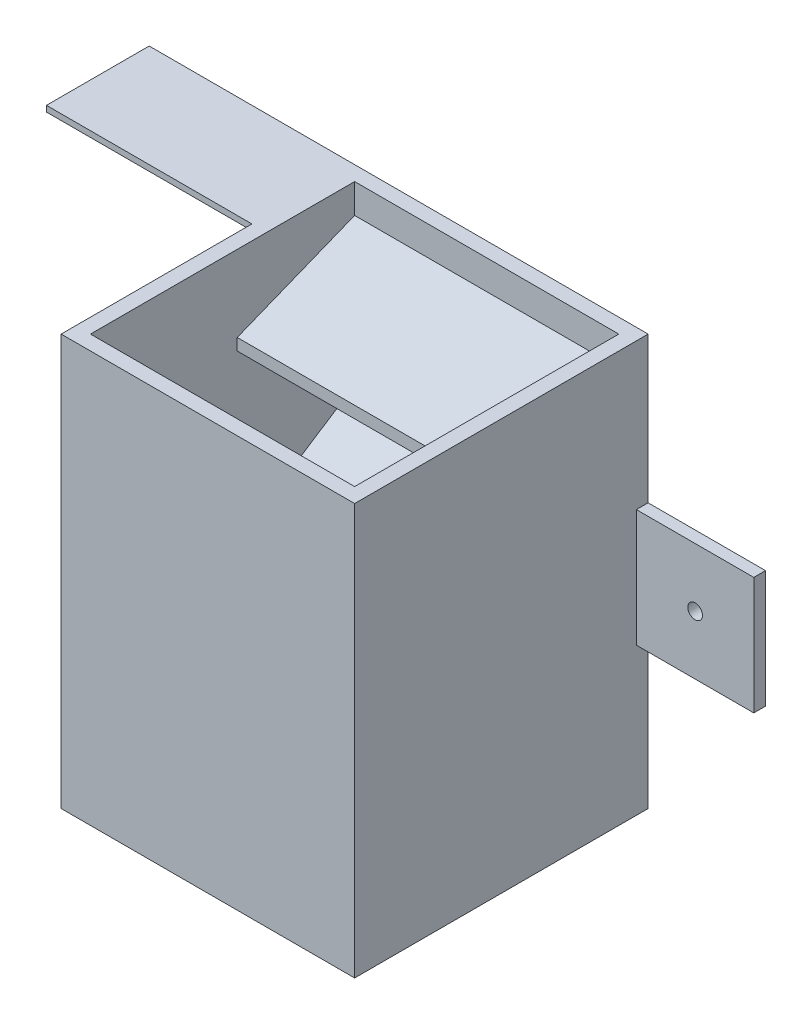
SolidWorks part; units mm, degrees
material "ABS"
ref_plane "Alzado" through (0, 0, 0) normal (0, 0, 1) x (1, 0, 0)
ref_plane "Planta" through (0, 0, 0) normal (0, 1, 0) x (1, 0, 0)
ref_plane "Vista lateral" through (0, 0, 0) normal (1, 0, 0) x (0, 0, -1)
sketch "Croquis2" plane through (0, 0, 0) normal (0, 1, 0) x (1, 0, 0)
  line L0 (-36.1972, 28.2218) -> (-36.1972, -21.7782)
  line L1 (-36.1972, -21.7782) -> (13.8028, -21.7782)
  line L2 (13.8028, -21.7782) -> (13.8028, 28.2218)
  line L3 (13.8028, 28.2218) -> (-36.1972, 28.2218)
  dimension "D1" = 50
  dimension "D2" = 50
extrude "Saliente-Extruir1" add sketch "Croquis2" along normal blind 70
sketch "Croquis3" plane through (0, 70, 0) normal (0, 1, 0) x (1, 0, 0)
  line L0 (-11.1972, 28.2218) -> (-11.1972, 25.7218) construction
  line L1 (13.8028, 28.2218) -> (-36.1972, 28.2218) construction
  line L2 (11.3028, 25.7218) -> (-33.6972, 25.7218)
  line L3 (-33.6972, 25.7218) -> (-33.6972, -19.2782)
  line L4 (-33.6972, -19.2782) -> (11.3028, -19.2782)
  line L5 (11.3028, -19.2782) -> (11.3028, 25.7218)
  point P7 (-11.1972, 25.7218)
  dimension "D1" = 2.5
  dimension "D2" = 45
  dimension "D3" = 45
extrude "Cortar-Extruir1" cut sketch "Croquis3" against normal blind 130
sketch "Croquis4" plane through (0, 0, -25.7218) normal (0, 0, 1) x (1, 0, 0)
  line L0 (-33.6972, 70) -> (-33.6972, 65) construction
  line L1 (-33.6972, 0) -> (-33.6972, 70) construction
  line L2 (-33.6972, 65) -> (11.3028, 65)
  line L3 (11.3028, 0) -> (11.3028, 70) construction
  line L4 (11.3028, 65) -> (11.3028, 55)
  line L5 (11.3028, 55) -> (-33.6972, 55)
  line L6 (-33.6972, 55) -> (-33.6972, 65)
  dimension "D1" = 5
  dimension "D2" = 10
extrude "Saliente-Extruir2" add sketch "Croquis4" along normal blind 20
sketch "Croquis5" plane through (-33.6972, 0, 0) normal (1, 0, 0) x (0, 0, -1)
  line L1 (5.7218, 65) -> (25.7218, 65)
  line L2 (5.7218, 65) -> (25.7218, 65) construction
  line L4 (5.7218, 65) -> (5.7218, 57)
  line L5 (5.7218, 65) -> (5.7218, 55) construction
  line L6 (5.7218, 57) -> (25.7218, 65)
  line L7 (25.7218, 55) -> (25.7218, 63)
  line L8 (25.7218, 63) -> (5.7218, 55)
  line L9 (5.7218, 55) -> (25.7218, 55)
  dimension "D1" = 8
  dimension "D2" = 8
extrude "Cortar-Extruir2" cut sketch "Croquis5" along normal blind 45
sketch "Croquis7" plane through (-33.6972, 0, 0) normal (1, 0, 0) x (0, 0, -1)
  line L0 (5.7218, 55) -> (-19.2782, 55) construction
  line L1 (-19.2782, 0) -> (-19.2782, 70) construction
  line L2 (-19.2782, 55) -> (-19.2782, 40)
  line L3 (-19.2782, 40) -> (0.7218, 40)
  line L4 (0.7218, 40) -> (0.7218, 55)
  line L5 (0.7218, 55) -> (-19.2782, 55)
  dimension "D1" = 15
  dimension "D2" = 20
extrude "Saliente-Extruir3" add sketch "Croquis7" along normal blind 45
sketch "Croquis8" plane through (-33.6972, 0, 0) normal (1, 0, 0) x (0, 0, -1)
  line L0 (0.7218, 55) -> (0.7218, 42)
  line L1 (0.7218, 40) -> (0.7218, 55) construction
  line L2 (0.7218, 55) -> (-19.2782, 55)
  line L3 (-19.2782, 55) -> (0.7218, 42)
  line L4 (0.7218, 40) -> (-19.2782, 40)
  line L5 (-19.2782, 40) -> (-19.2782, 53)
  line L6 (-19.2782, 53) -> (0.7218, 40)
  dimension "D1" = 13
  dimension "D2" = 13
extrude "Cortar-Extruir3" cut sketch "Croquis8" along normal blind 45
sketch "Croquis9" plane through (-33.6972, 0, 0) normal (1, 0, 0) x (0, 0, -1)
  line L0 (0.7218, 40) -> (25.7218, 40) construction
  line L1 (25.7218, 0) -> (25.7218, 63) construction
  line L2 (25.7218, 40) -> (25.7218, 25)
  line L3 (25.7218, 25) -> (5.7218, 25)
  line L4 (5.7218, 25) -> (5.7218, 40)
  line L5 (5.7218, 40) -> (25.7218, 40)
  dimension "D1" = 15
  dimension "D2" = 20
extrude "Saliente-Extruir4" add sketch "Croquis9" along normal blind 45
sketch "Croquis10" plane through (-33.6972, 0, 0) normal (1, 0, 0) x (0, 0, -1)
  line L0 (5.7218, 40) -> (5.7218, 27)
  line L1 (5.7218, 40) -> (5.7218, 25) construction
  line L2 (5.7218, 40) -> (25.7218, 40)
  line L3 (25.7218, 40) -> (5.7218, 27)
  line L4 (5.7218, 25) -> (25.7218, 25)
  line L5 (25.7218, 25) -> (25.7218, 38)
  line L6 (25.7218, 38) -> (5.7218, 25)
  dimension "D1" = 13
  dimension "D2" = 13
extrude "Cortar-Extruir4" cut sketch "Croquis10" along normal blind 45
sketch "Croquis16" plane through (0, 70, 0) normal (0, 1, 0) x (1, 0, 0)
  line L11 (-36.1972, 28.2218) -> (-36.1972, -21.7782) construction
  line L14 (38.8028, 28.2218) -> (-201.1972, 28.2218) construction
  line L15 (-71.1972, 28.2218) -> (-36.1972, 28.2218)
  line L16 (-36.1972, 28.2218) -> (-36.1972, 10.7218)
  line L17 (-36.1972, 10.7218) -> (-71.1972, 10.7218)
  line L18 (-71.1972, 10.7218) -> (-71.1972, 28.2218)
  dimension "D1" = 17.5
  dimension "D2" = 35
extrude "Saliente-Extruir7" add sketch "Croquis16" against normal blind 1
sketch "Croquis17" plane through (0, 0, -28.2218) normal (0, 0, -1) x (-1, 0, 0)
  line L0 (-13.8028, 25.1036) -> (-13.8028, 45.1036)
  line L1 (-13.8028, 70) -> (-13.8028, 0) construction
  line L2 (-13.8028, 45.1036) -> (-33.8028, 45.1036)
  line L3 (-33.8028, 45.1036) -> (-33.8028, 25.1036)
  line L4 (-33.8028, 25.1036) -> (-13.8028, 25.1036)
  line L5 (36.1972, 25.1036) -> (56.1972, 25.1036)
  line L6 (36.1972, 69) -> (36.1972, 0) construction
  line L7 (56.1972, 25.1036) -> (56.1972, 45.1036)
  line L8 (56.1972, 45.1036) -> (36.1972, 45.1036)
  line L9 (36.1972, 45.1036) -> (36.1972, 25.1036)
  line L10 (-13.8028, 45.1036) -> (-33.8028, 25.1036) construction
  line L11 (36.1972, 45.1036) -> (56.1972, 25.1036) construction
  circle A0 centre (-23.8028, 35.1036) radius 1.25
  circle A1 centre (46.1972, 35.1036) radius 1.25
  point P5 (-13.8028, 35.1036)
  dimension "D5" = 2.5
  dimension "D6" = 2.5
  dimension "D1" = 20
  dimension "D2" = 20
  dimension "D3" = 20
  dimension "D4" = 20
extrude "Saliente-Extruir8" add sketch "Croquis17" against normal blind 2
